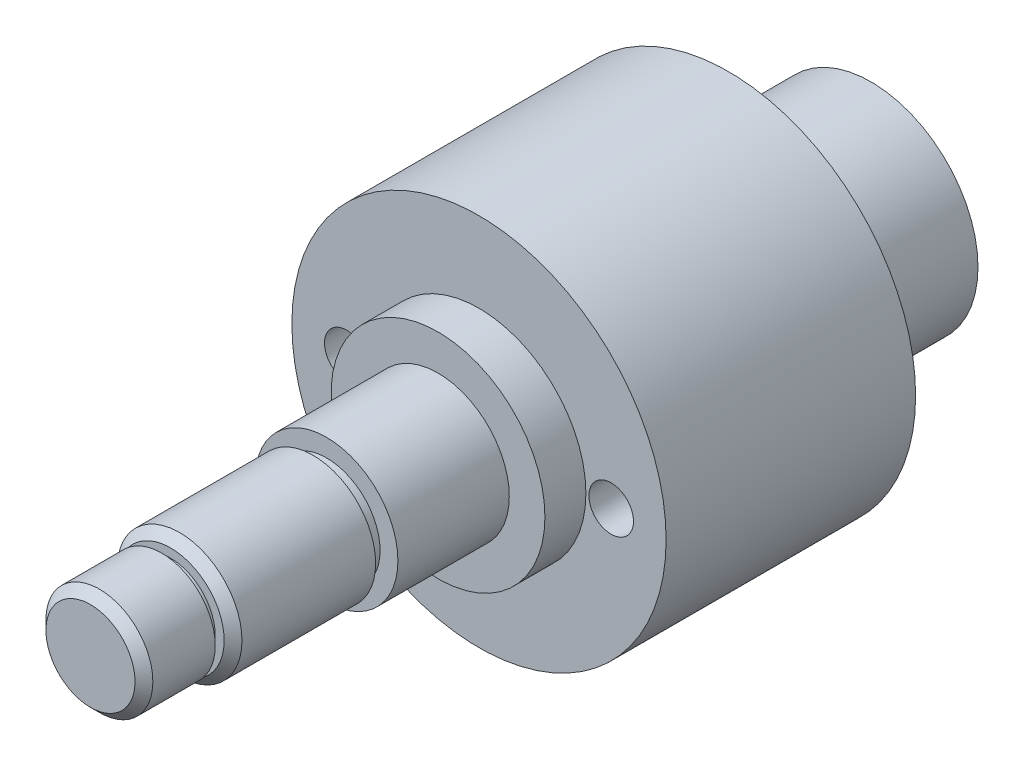
SolidWorks part; units mm, degrees
ref_plane "Plan de face" through (0, 0, 0) normal (0, 0, 1) x (1, 0, 0)
ref_plane "Plan de dessus" through (0, 0, 0) normal (0, 1, 0) x (1, 0, 0)
ref_plane "Plan de droite" through (0, 0, 0) normal (1, 0, 0) x (0, 0, -1)
sketch "Esquisse1" plane through (0, 0, 0) normal (0, 0, 1) x (1, 0, 0)
  circle A0 centre (0, 0) radius 6
  dimension "D1" = 12
extrude "Boss.-Extru.1" add sketch "Esquisse1" along normal blind 8
sketch "Esquisse2" plane through (0, 0, 8) normal (0, 0, 1) x (1, 0, 0)
  circle A0 centre (0, 0) radius 10.5
  circle A1 centre (-7.4186, -0.0266) radius 1.25
  circle A2 centre (7.4186, -0.0266) radius 1.25
  dimension "D1" = 21
  dimension "D2" = 2.5
  dimension "D3" = 2.5
extrude "Boss.-Extru.2" add sketch "Esquisse2" along normal blind 14
sketch "Esquisse3" plane through (0, 0, 22) normal (0, 0, 1) x (1, 0, 0)
  circle A0 centre (0, 0) radius 6
  dimension "D1" = 12
extrude "Boss.-Extru.3" add sketch "Esquisse3" along normal blind 2.3
sketch "Esquisse4" plane through (0, 0, 24.3) normal (0, 0, 1) x (1, 0, 0)
  circle A0 centre (0, 0) radius 4
  dimension "D1" = 8
extrude "Boss.-Extru.4" add sketch "Esquisse4" along normal blind 6.25
sketch "Esquisse5" plane through (0, 0, 30.55) normal (0, 0, 1) x (1, 0, 0)
  circle A0 centre (0, 0) radius 3
  dimension "D1" = 6
extrude "Boss.-Extru.5" add sketch "Esquisse5" along normal blind 0.75
sketch "Esquisse7" plane through (0, 0, 31.3) normal (0, 0, 1) x (1, 0, 0)
  circle A0 centre (0, 0) radius 3.5
  dimension "D1" = 7
extrude "Boss.-Extru.6" add sketch "Esquisse7" along normal blind 8
sketch "Esquisse8" plane through (0, 0, 39.3) normal (0, 0, 1) x (1, 0, 0)
  circle A0 centre (0, 0) radius 2.5
  dimension "D1" = 5
extrude "Boss.-Extru.7" add sketch "Esquisse8" along normal blind 0.5
sketch "Esquisse9" plane through (0, 0, 39.8) normal (0, 0, 1) x (1, 0, 0)
  circle A0 centre (0, 0) radius 3
  dimension "D1" = 6
extrude "Boss.-Extru.8" add sketch "Esquisse9" along normal blind 4
sketch "Esquisse10" plane through (0, 0, 0) normal (0, 0, -1) x (-1, 0, 0)
  circle A0 centre (0, 0) radius 4.75
  dimension "D1" = 9.5
extrude "Enlèv. mat.-Extru.1" cut sketch "Esquisse10" against normal blind 21
chamfer "Chanfrein1" distance 0.5 angle 45 1 edges at (3.5, 0, 39.3)
chamfer "Chanfrein2" distance 0.5 angle 45 1 edges at (3, 0, 43.8)
